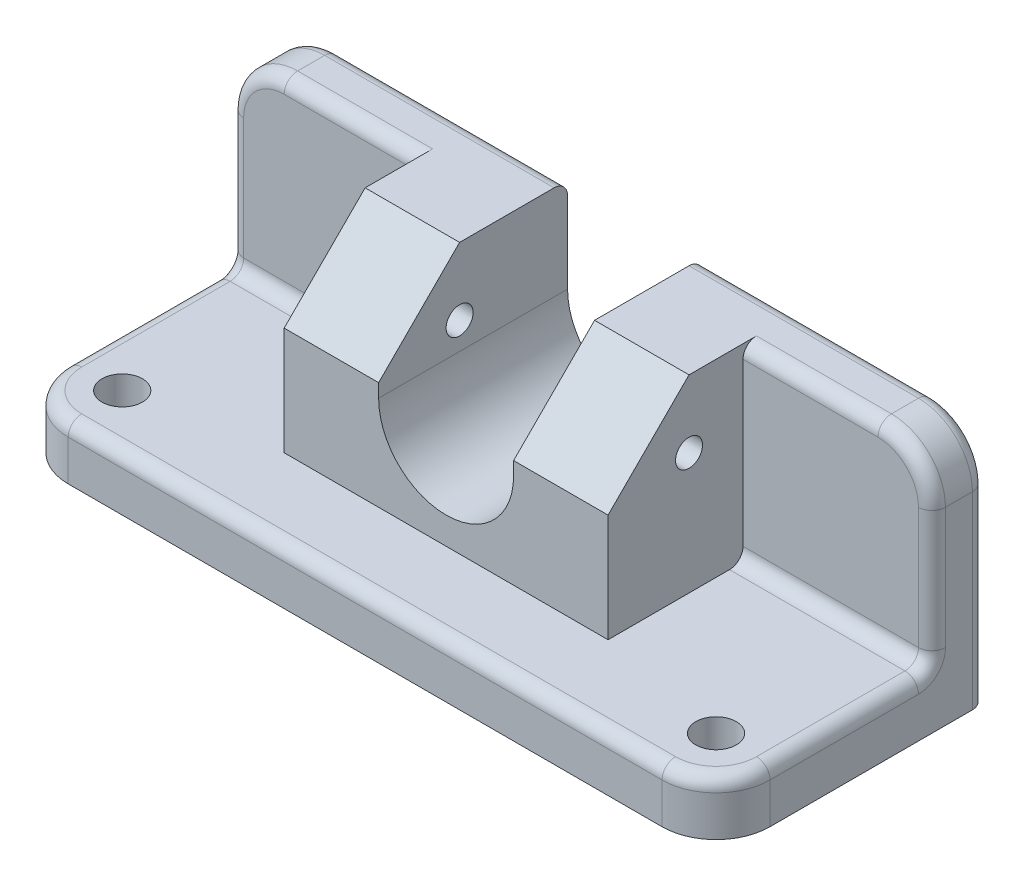
SolidWorks part; units mm, degrees
ref_plane "Front Plane" through (0, 0, 0) normal (0, 0, 1) x (1, 0, 0)
ref_plane "Top Plane" through (0, 0, 0) normal (0, 1, 0) x (1, 0, 0)
ref_plane "Right Plane" through (0, 0, 0) normal (1, 0, 0) x (0, 0, -1)
sketch "Sketch1" plane through (0, 0, 0) normal (0, 1, 0) x (1, 0, 0)
  line L1 (-65, -50) -> (65, -50)
  line L2 (-65, -50) -> (-65, 50)
  line L3 (-65, 50) -> (65, 50)
  line L4 (65, -50) -> (65, 50)
  line L5 (-65, -50) -> (65, 50) construction
  line L6 (-65, 50) -> (65, -50) construction
  point P0 (0, 0)
  dimension "D1" = 100
  dimension "D2" = 130
extrude "Boss-Extrude1" add sketch "Sketch1" along normal blind 20
sketch "Sketch2" plane through (0, 20, 0) normal (0, 1, 0) x (1, 0, 0)
  line L0 (65, -50) -> (65, 50) construction
  line L1 (-65, 50) -> (65, 50)
  line L2 (-65, 50) -> (-65, 30)
  line L3 (-65, 30) -> (65, 30)
  line L4 (65, 50) -> (65, 30)
  dimension "D1" = 20
extrude "Boss-Extrude2" add sketch "Sketch2" along normal blind 70
fillet "Fillet1" radius 20 2 edges at (-65, 10, 50) (-65, 90, -40)
sketch "Sketch3" plane through (0, 0, -30) normal (0, 0, 1) x (1, 0, 0)
  line L0 (-45, 90) -> (65, 90) construction
  line L1 (65, 20) -> (5, 20)
  line L2 (65, 20) -> (65, 90)
  line L3 (65, 90) -> (5, 90)
  line L4 (5, 20) -> (5, 90)
  dimension "D1" = 60
extrude "Boss-Extrude3" add sketch "Sketch3" along normal blind 50
sketch "Sketch4" plane through (0, 0, 20) normal (0, 0, 1) x (1, 0, 0)
  line L0 (40, 90) -> (40, 55)
  line L1 (65, 90) -> (5, 90) construction
  line L2 (65, 20) -> (65, 90) construction
  line L7 (65, 20) -> (65, 90)
  line L8 (65, 90) -> (5, 90)
  line L9 (5, 90) -> (5, 20)
  line L10 (5, 20) -> (65, 20)
  line L11 (65, 30) -> (65, 90)
  line L12 (65, 90) -> (40, 90)
  arc A0 (40, 55) -> (65, 30) centre (65, 55) ccw
  dimension "D2" = 25
  dimension "D1" = 25
  dimension "D3" = 35
  dimension "D4" = 0
extrude "Cut-Extrude1" cut sketch "Sketch4" against normal through all
chamfer "Chamfer1" distance 30 angle 45 1 edges at (22.5, 90, 20)
hole_wizard "Ø10.0 (10) Diameter Hole1" positions "Sketch6" profile "Sketch5" hole size "Ø10.0" standard "ANSI Metric" end condition through all
sketch "Sketch6" plane through (5, 0, 0) normal (-1, 0, 0) x (0, 0, 1)
  line L0 (20, 60) -> (20, 20) construction
  line L1 (20, 20) -> (-30, 20) construction
  point P0 (-10, 65)
  dimension "D1" = 30
  dimension "D2" = 45
sketch "Sketch5" plane through (5, 65, -10) normal (0, 1, 0) x (0, 0, 1)
  line L0 (0, 0) -> (0, 60)
  line L1 (0, 60) -> (5, 60)
  line L2 (5, 60) -> (5, 0)
  line L5 (5, 0) -> (0, 0)
  line L11 (0, -6.35) -> (0, 107.95) construction
  dimension "Thru Hole Dia." = 10
  dimension "Thru Hole Depth" = 60
hole_wizard "Ø15.0 (15) Diameter Hole1" positions "Sketch8" profile "Sketch7" hole size "Ø15.0" standard "ANSI Metric" end condition through all
sketch "Sketch8" plane through (0, 20, 0) normal (0, 1, 0) x (1, 0, 0)
  point P0 (-45, -30)
sketch "Sketch7" plane through (-45, 20, 30) normal (1, 0, 0) x (0, 0, 1)
  line L0 (0, 0) -> (0, 20)
  line L1 (0, 20) -> (7.5, 20)
  line L2 (7.5, 20) -> (7.5, 0)
  line L5 (7.5, 0) -> (0, 0)
  line L11 (0, -6.35) -> (0, 107.95) construction
  dimension "Thru Hole Dia." = 15
  dimension "Thru Hole Depth" = 20
fillet "Fillet2" radius 5 10 edges at (10, 20, 50) (-65, 35, -50) (-2.5, 90, -50) (-20, 90, -30) (-59.1421, 20, 44.1421) (-59.1421, 84.1421, -50) (-59.1421, 84.1421, -30)
mirror "鏡射1" about plane through (65, 20, 50) normal (-1, 0, 0) of bodies 106
